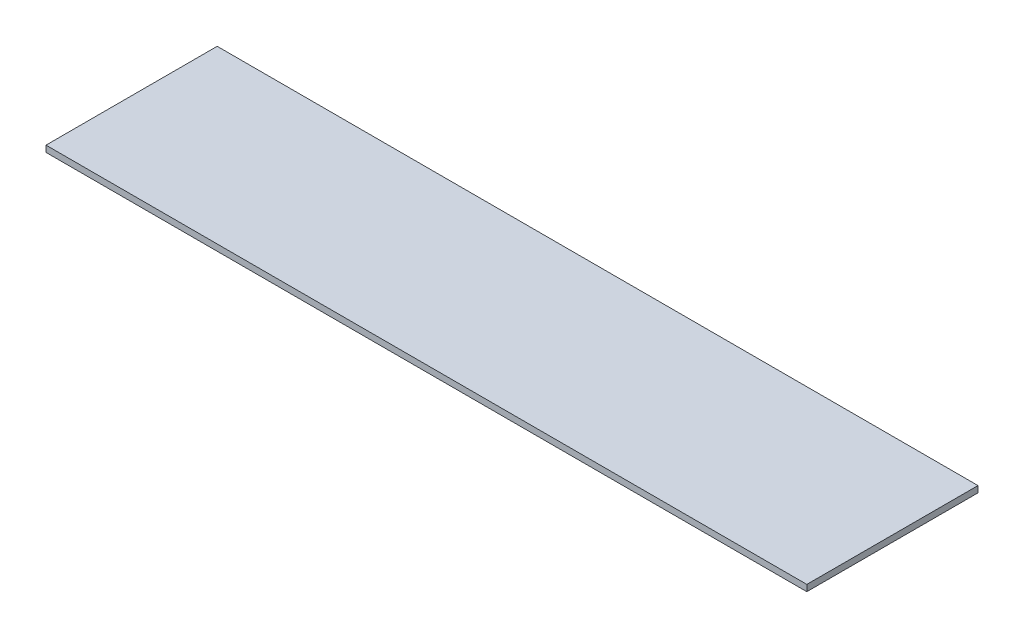
SolidWorks part; units mm, degrees
ref_plane "Front Plane" through (0, 0, 0) normal (0, 0, 1) x (1, 0, 0)
ref_plane "Top Plane" through (0, 0, 0) normal (0, 1, 0) x (1, 0, 0)
ref_plane "Right Plane" through (0, 0, 0) normal (1, 0, 0) x (0, 0, -1)
sketch "Sketch1" plane through (0, 0, 0) normal (0, 1, 0) x (1, 0, 0)
  line L1 (0, 0) -> (120, 0)
  line L2 (0, 0) -> (0, 27)
  line L3 (0, 27) -> (120, 27)
  line L4 (120, 0) -> (120, 27)
  dimension "D1" = 120
  dimension "D2" = 27
extrude "Boss-Extrude1" add sketch "Sketch1" along normal blind 1
sketch "Sketch2" plane through (0, 1, 0) normal (0, 1, 0) x (1, 0, 0)
  text T0 "GNSS Dual u.FL Antenna"
